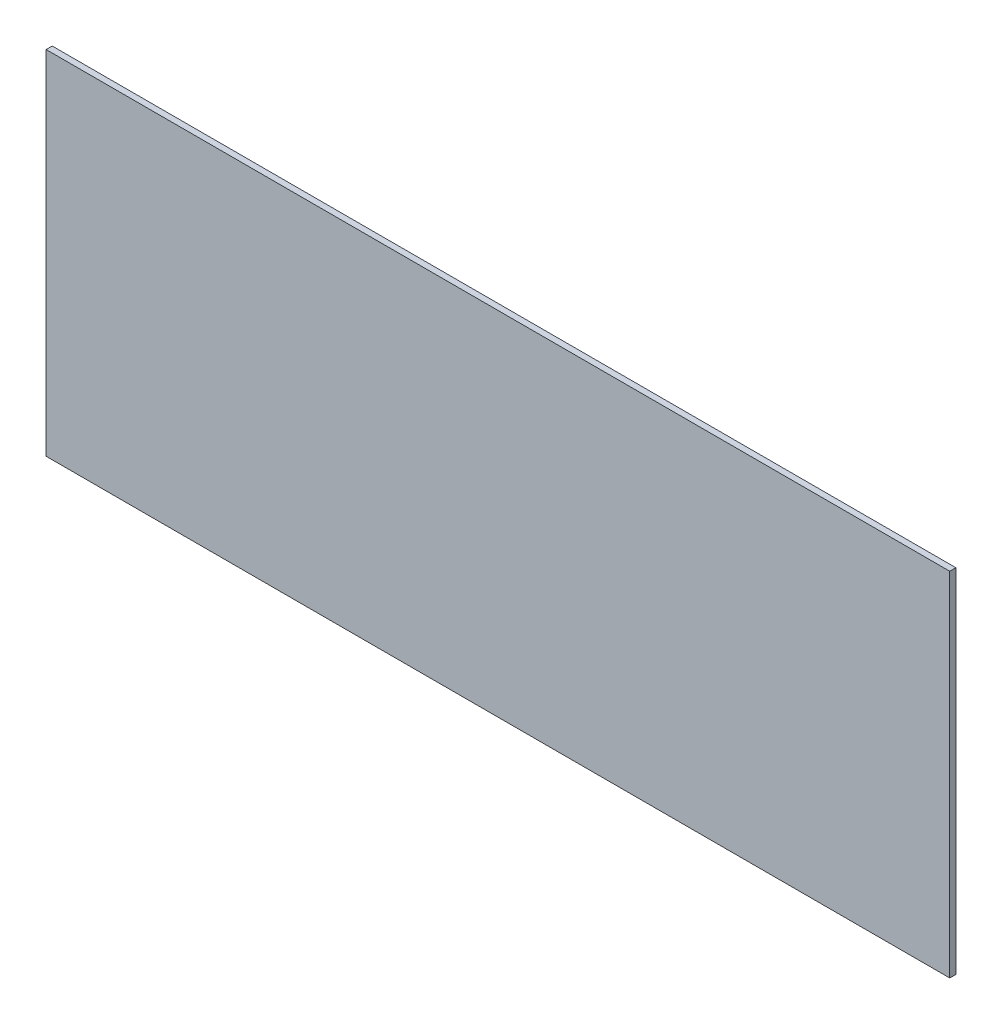
SolidWorks part; units mm, degrees
ref_plane "Front Plane" through (0, 0, 0) normal (0, 0, 1) x (1, 0, 0)
ref_plane "Top Plane" through (0, 0, 0) normal (0, 1, 0) x (1, 0, 0)
ref_plane "Right Plane" through (0, 0, 0) normal (1, 0, 0) x (0, 0, -1)
other "Configuration Table"
sketch "Sketch1" plane through (0, 0, 0) normal (0, 0, 1) x (1, 0, 0)
  line L1 (25, 25) -> (615, 25)
  line L2 (25, 25) -> (25, 255)
  line L3 (25, 255) -> (615, 255)
  line L4 (615, 25) -> (615, 255)
extrude "FKAP_cam_ic_4mm_1" add sketch "Sketch1" along normal blind 4 from offset 22 separate body
